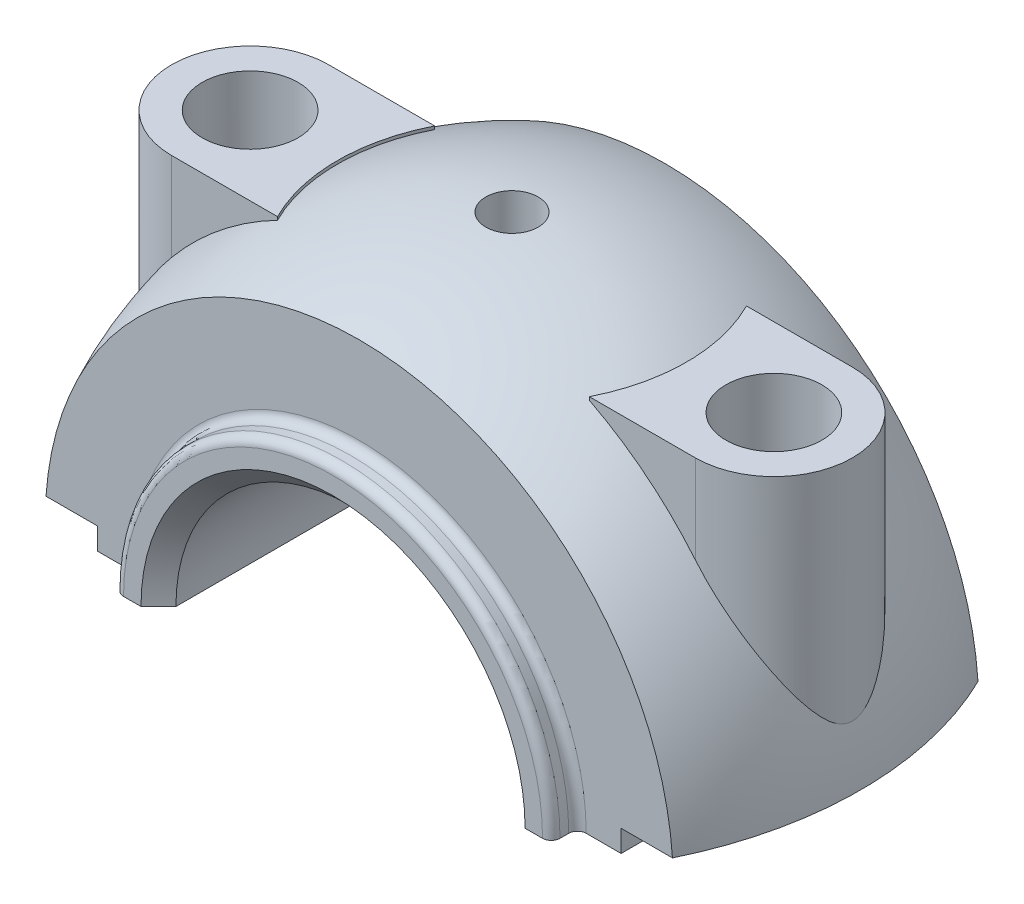
SolidWorks part; units mm, degrees
ref_plane "Front Plane" through (0, 0, 0) normal (0, 0, 1) x (1, 0, 0)
ref_plane "Top Plane" through (0, 0, 0) normal (0, 1, 0) x (1, 0, 0)
ref_plane "Right Plane" through (0, 0, 0) normal (1, 0, 0) x (0, 0, -1)
sketch "Sketch1" plane through (0, 0, 0) normal (0, 1, 0) x (1, 0, 0)
  line L0 (0, 0) -> (-53.5002, 0) construction
  line L1 (0, 0) -> (0, 31.6035) construction
  line L2 (-20, 20.5) -> (-20, -20.5)
  line L3 (-20, -20.5) -> (-25, -20.5)
  line L4 (-25, -20.5) -> (-25, -17.5)
  line L5 (-25, -17.5) -> (-35.9687, -17.5)
  line L6 (-25, 20.5) -> (-25, 17.5)
  line L7 (-20, 20.5) -> (-25, 20.5)
  line L8 (-25, 17.5) -> (-35.9687, 17.5)
  arc A0 (-35.9687, 17.5) -> (-35.9687, -17.5) centre (0, 0) ccw
  dimension "D1" = 80
  dimension "D2" = 20
  dimension "D3" = 41
  dimension "D4" = 3
  dimension "D6" = 5
revolve "Revolve1" add sketch "Sketch1" angle 180 about L1
ref_plane "Plane1" through (0, 35, 0) normal (0, -1, 0) x (-1, 0, 0)
sketch "Sketch2" plane through (0, 35, 0) normal (0, -1, 0) x (-1, 0, 0)
  line L0 (0, 0) -> (21, 0) construction
  line L1 (0, 20) -> (0, 28.1339) construction
  line L2 (30, 9) -> (17.8606, 9)
  line L3 (30, -9) -> (17.8606, -9)
  line L4 (39, 0) -> (49.0179, 0) construction
  arc A0 (17.8606, -9) -> (17.8606, 9) centre (0, 0) ccw
  arc A1 (30, -9) -> (30, 9) centre (30, 0) ccw
  dimension "D1" = 40
  dimension "D3" = 18
  dimension "D2" = 30
extrude "Boss-Extrude1" add sketch "Sketch2" along normal up to next
sketch "Sketch3" plane through (0, 0, 0) normal (0, -1, 0) x (1, 0, 0)
  circle A0 centre (-30, 0) radius 5.5
  dimension "D1" = 11
  dimension "D2" = 30
extrude "Cut-Extrude1" cut sketch "Sketch3" against normal through all
mirror "Mirror1" about plane through (0, 0, 0) normal (1, 0, 0) of "Boss-Extrude1", "Cut-Extrude1"
sketch "Sketch4" plane through (0, 0, 0) normal (0, -1, 0) x (1, 0, 0)
  circle A0 centre (0, 0) radius 3
  dimension "D1" = 6
extrude "Cut-Extrude2" cut sketch "Sketch4" against normal through all
sketch "Sketch5" plane through (0, 0, 0) normal (0, 0, 1) x (1, 0, 0)
  line L0 (-35.9687, 0) -> (-25, 0) construction
  line L1 (-30, 0) -> (-48.1964, 0)
  line L2 (-30, 0) -> (-30, 2.5)
  line L3 (-30, 2.5) -> (-48.1964, 2.5)
  line L4 (-48.1964, 0) -> (-48.1964, 2.5)
  line L5 (35.9687, 0) -> (25, 0) construction
  line L6 (30, 0) -> (49.029, 0)
  line L7 (30, 0) -> (30, 2.5)
  line L8 (30, 2.5) -> (49.029, 2.5)
  line L9 (49.029, 0) -> (49.029, 2.5)
  dimension "D1" = 2.5
  dimension "D2" = 30
  dimension "D3" = 2.5
  dimension "D4" = 30
extrude "Cut-Extrude3" cut sketch "Sketch5" against normal through all both and the other way through all
chamfer "Chamfer1" distance 2 angle 45 2 edges at (0, 20, -20.5) (0, 20, 20.5)
fillet "Fillet1" radius 1 4 edges at (0, 25, -20.5) (0, 25, -17.5) (0, 25, 20.5) (0, 25, 17.5)
